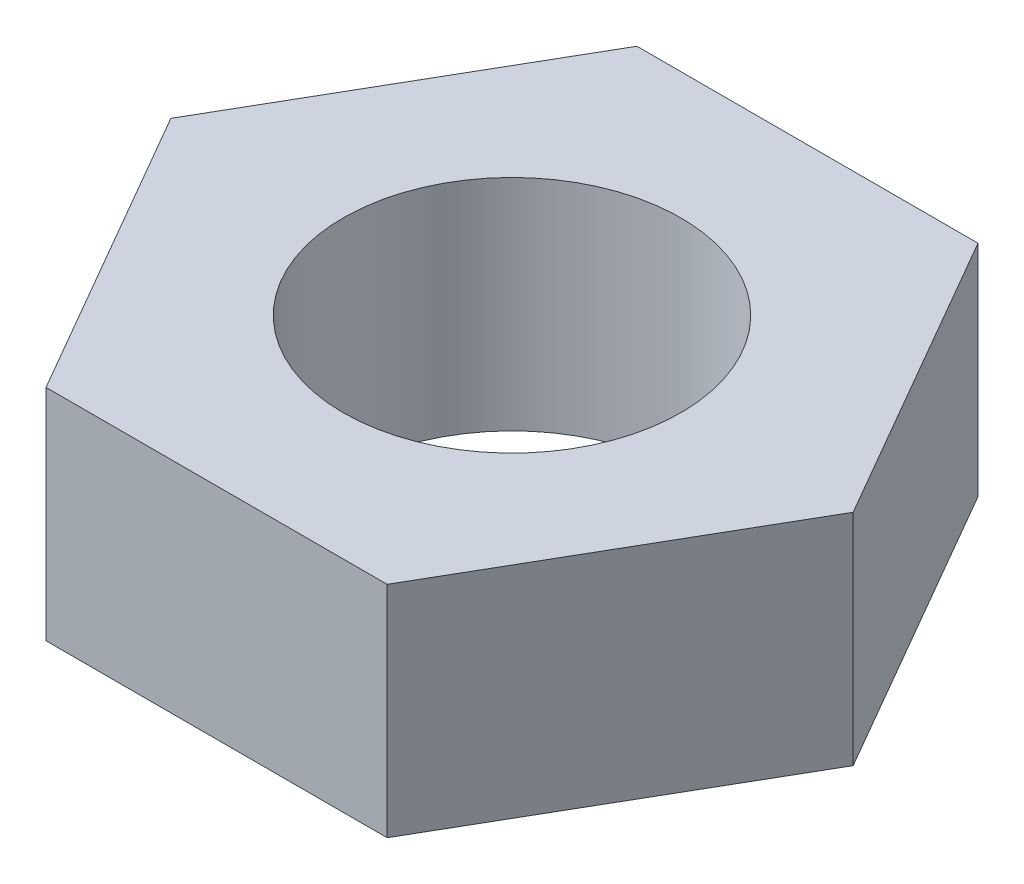
SolidWorks part; units mm, degrees
ref_plane "Plan de face" through (0, 0, 0) normal (0, 0, 1) x (1, 0, 0)
ref_plane "Plan de dessus" through (0, 0, 0) normal (0, 1, 0) x (1, 0, 0)
ref_plane "Plan de droite" through (0, 0, 0) normal (1, 0, 0) x (0, 0, -1)
sketch "Esquisse1" plane through (0, 0, 0) normal (0, 1, 0) x (1, 0, 0)
  line L1 (4.0415, 0) -> (2.0207, 3.5)
  line L2 (2.0207, 3.5) -> (-2.0207, 3.5)
  line L3 (-2.0207, 3.5) -> (-4.0415, 0)
  line L4 (-4.0415, 0) -> (-2.0207, -3.5)
  line L5 (-2.0207, -3.5) -> (2.0207, -3.5)
  line L6 (2.0207, -3.5) -> (4.0415, 0)
  circle A0 centre (0, 0) radius 3.5 construction
  circle A1 centre (0, 0) radius 2
  dimension "D1" = 7
  dimension "D2" = 4
extrude "Boss.-Extru.1" add sketch "Esquisse1" along normal blind 2.6
